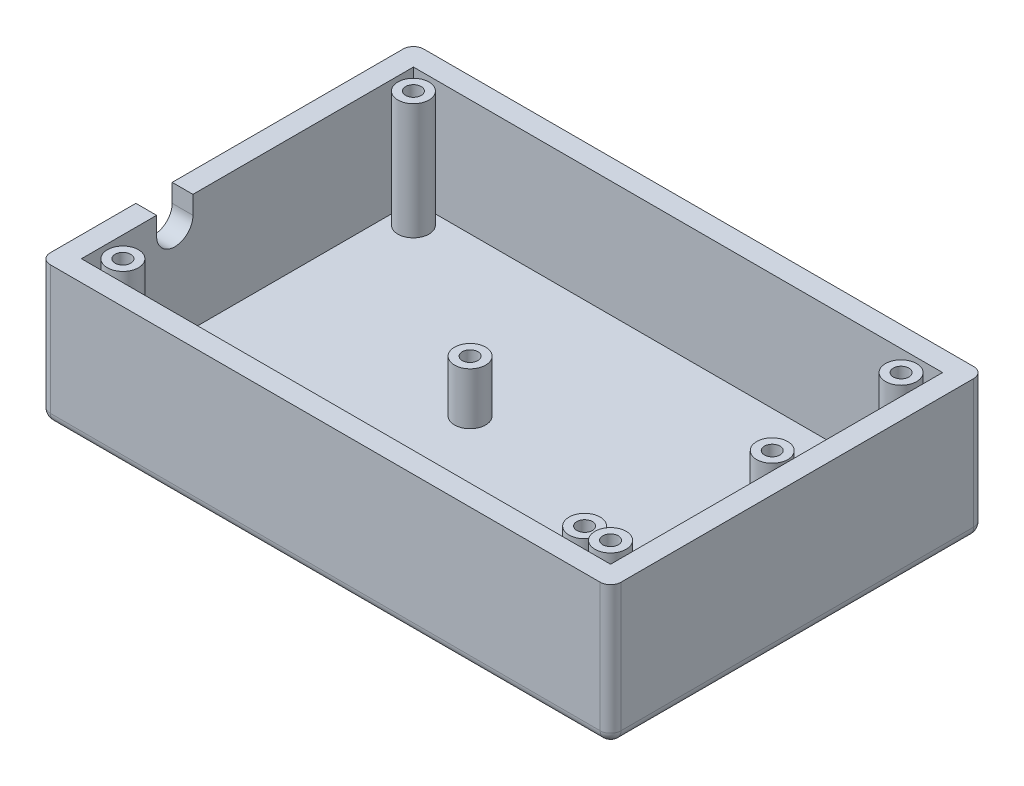
SolidWorks part; units mm, degrees
ref_plane "Front Plane" through (0, 0, 0) normal (0, 0, 1) x (1, 0, 0)
ref_plane "Top Plane" through (0, 0, 0) normal (0, 1, 0) x (1, 0, 0)
ref_plane "Right Plane" through (0, 0, 0) normal (1, 0, 0) x (0, 0, -1)
sketch "Sketch2" plane through (0, 0, 0) normal (0, 1, 0) x (1, 0, 0)
  line L1 (0, 0) -> (69.85, 0)
  line L2 (0, 0) -> (0, 45.72)
  line L3 (0, 45.72) -> (69.85, 45.72)
  line L4 (69.85, 0) -> (69.85, 45.72)
  dimension "D1" = 45.72
  dimension "D2" = 69.85
extrude "Boss-Extrude1" add sketch "Sketch2" along normal blind 17.018
sketch "Sketch3" plane through (0, 17.018, 0) normal (0, 1, 0) x (1, 0, 0)
  line L1 (2.54, 43.18) -> (67.31, 43.18)
  line L2 (2.54, 43.18) -> (2.54, 2.54)
  line L3 (2.54, 2.54) -> (67.31, 2.54)
  line L4 (67.31, 43.18) -> (67.31, 2.54)
  line L5 (0, 45.72) -> (0, 0) construction
  line L6 (69.85, 45.72) -> (0, 45.72) construction
  line L7 (69.85, 0) -> (69.85, 45.72) construction
  line L8 (0, 0) -> (69.85, 0) construction
  dimension "D1" = 2.54
  dimension "D2" = 2.54
  dimension "D3" = 2.54
  dimension "D4" = 2.54
  dimension "D5" = 40.64
extrude "Cut-Extrude1" cut sketch "Sketch3" against normal blind 14.224
sketch "Sketch9" plane through (0, 2.794, 0) normal (0, 1, 0) x (1, 0, 0)
  line L0 (67.31, 43.18) -> (67.31, 35.56)
  line L1 (67.31, 2.54) -> (67.31, 43.18) construction
  line L2 (67.31, 43.18) -> (66.675, 43.18)
  line L3 (67.31, 43.18) -> (2.54, 43.18) construction
  line L4 (66.675, 43.18) -> (66.675, 35.56)
  line L5 (66.675, 35.56) -> (67.31, 35.56)
  dimension "D1" = 7.62
  dimension "D2" = 0.635
sketch "Sketch13" plane through (0, 2.794, 0) normal (0, 1, 0) x (1, 0, 0)
  circle A0 centre (57.277, 32.3596) radius 1.905
  circle A1 centre (53.7972, 12.8778) radius 1.905
  circle A2 centre (28.7782, 23.876) radius 1.905
  dimension "D1" = 3.81
  dimension "D2" = 3.81
  dimension "D3" = 3.81
  dimension "D4" = 3.2004
  dimension "D5" = 9.398
  dimension "D6" = 19.4818
  dimension "D7" = 3.4798
  dimension "D8" = 8.4836
  dimension "D9" = 28.4988
extrude "Boss-Extrude5" add sketch "Sketch13" along normal blind 6.35
sketch "Sketch14" plane through (0, 9.144, 0) normal (0, 1, 0) x (1, 0, 0)
  circle A0 centre (57.277, 32.3596) radius 0.9525
  circle A1 centre (53.7972, 12.8778) radius 0.9525
  circle A2 centre (28.7782, 23.876) radius 0.9525
  dimension "D1" = 1.905
  dimension "D2" = 1.905
  dimension "D3" = 1.905
extrude "Cut-Extrude4" cut sketch "Sketch14" against normal up to surface (6.35 mm away) up to face at (28.7782, 2.794, -21.971)
sketch "Sketch17" plane through (0, 0, 0) normal (-1, 0, 0) x (0, 0, 1)
  line L0 (-45.72, 17.018) -> (0, 17.018) construction
  line L1 (-45.72, 17.018) -> (-45.72, 0) construction
  line L2 (-16.1925, 14.7955) -> (-16.1925, 17.018)
  line L3 (-11.7475, 14.7955) -> (-11.7475, 17.018)
  line L4 (-11.7475, 17.018) -> (-16.1925, 17.018)
  arc A0 (-16.1925, 14.7955) -> (-11.7475, 14.7955) centre (-13.97, 14.7955) ccw
  dimension "D1" = 4.445
  dimension "D2" = 31.75
extrude "Cut-Extrude5" cut sketch "Sketch17" against normal up to surface (2.54 mm away) up to face at (2.54, 9.906, -22.86)
fillet "Fillet1" radius 1.27 8 edges at (34.925, 0, 0) (69.85, 0, -22.86) (34.925, 0, -45.72) (0, 0, -22.86) (0, 8.509, -45.72) (0, 8.509, 0) (69.85, 8.509, -45.72) (69.85, 8.509, 0)
sketch "Sketch18" plane through (0, 2.794, 0) normal (0, 1, 0) x (1, 0, 0)
  line L0 (2.54, 43.18) -> (2.54, 16.1925) construction
  line L1 (67.31, 2.54) -> (67.31, 43.18) construction
  line L5 (67.31, 43.18) -> (2.54, 43.18) construction
  line L7 (2.54, 2.54) -> (67.31, 2.54) construction
  line L8 (2.54, 2.54) -> (67.31, 2.54) construction
  line L9 (2.54, 43.18) -> (2.54, 2.54) construction
  line L10 (67.31, 43.18) -> (2.54, 43.18) construction
  line L11 (67.31, 2.54) -> (67.31, 43.18) construction
  circle A0 centre (5.08, 40.64) radius 1.905
  circle A1 centre (64.77, 40.64) radius 1.905
  circle A2 centre (5.08, 5.08) radius 1.905
  circle A3 centre (64.77, 5.08) radius 1.905
  point P14 (5.08, 5.08)
  dimension "D1" = 3.81
  dimension "D2" = 3.81
  dimension "D3" = 3.81
  dimension "D4" = 3.81
  dimension "D5" = 2.54
  dimension "D6" = 2.54
  dimension "D7" = 2.54
  dimension "D8" = 2.54
  dimension "D9" = 2.54
  dimension "D10" = 2.54
  dimension "D11" = 2.54
  dimension "D12" = 2.54
extrude "Boss-Extrude11" add sketch "Sketch18" along normal up to surface (14.224 mm away) up to face at (26.5113, 17.018, -20.6375)
sketch "Sketch19" plane through (0, 17.018, 0) normal (0, 1, 0) x (1, 0, 0)
  circle A0 centre (5.08, 40.64) radius 0.9525
  circle A1 centre (64.77, 40.64) radius 0.9525
  circle A2 centre (64.77, 5.08) radius 0.9525
  circle A3 centre (5.08, 5.08) radius 0.9525
  dimension "D1" = 1.905
  dimension "D2" = 1.905
  dimension "D3" = 1.905
  dimension "D4" = 1.905
extrude "Cut-Extrude6" cut sketch "Sketch19" against normal blind 6.35
sketch "Switch And LED pos" plane through (0, 2.794, 0) normal (0, 1, 0) x (1, 0, 0)
  line L0 (57.277, 32.3596) -> (23.7998, 32.3596)
  line L1 (23.7998, 32.3596) -> (23.7998, 17.78)
  line L2 (57.277, 32.3596) -> (62.7634, 32.3596)
  line L3 (62.7634, 32.3596) -> (62.7634, 14.6558)
  dimension "D1" = 33.4772
  dimension "D2" = 14.5796
  dimension "D3" = 5.4864
  dimension "D4" = 17.7038
